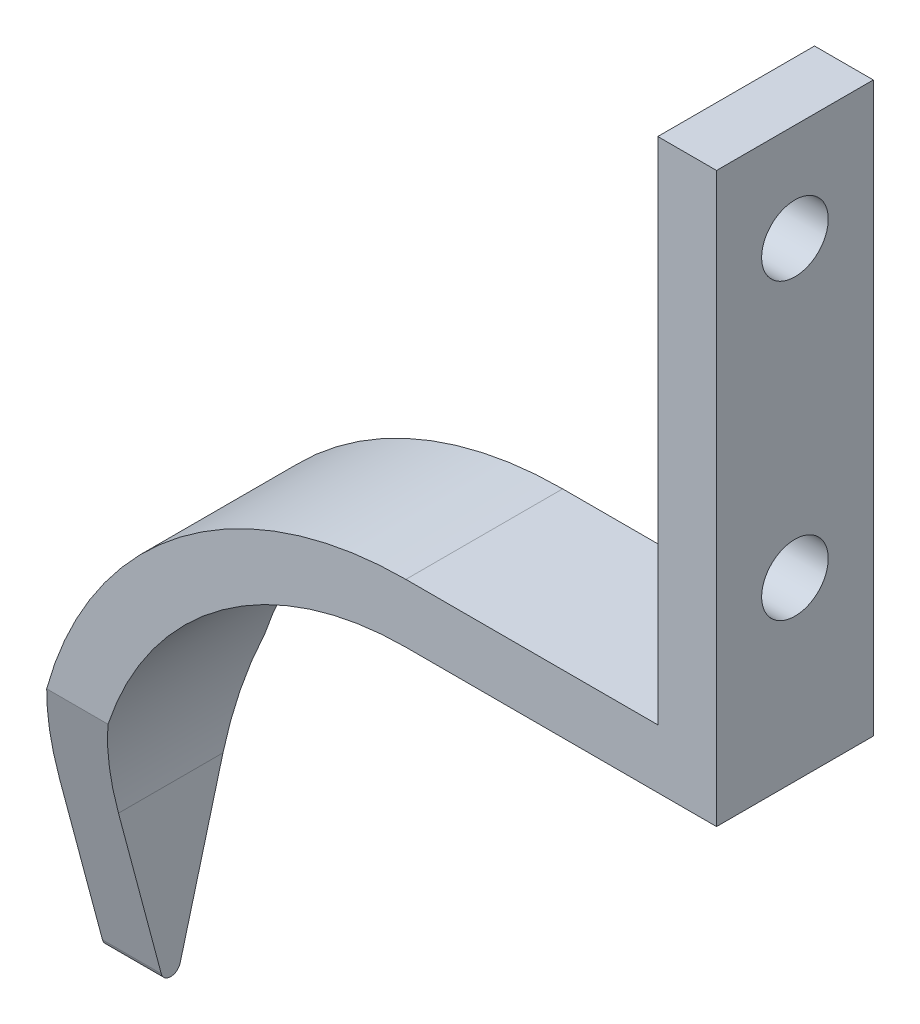
SolidWorks part; units mm, degrees
ref_plane "Front" through (0, 0, 0) normal (0, 0, 1) x (1, 0, 0)
ref_plane "Top" through (0, 0, 0) normal (0, 1, 0) x (1, 0, 0)
ref_plane "Right" through (0, 0, 0) normal (1, 0, 0) x (0, 0, -1)
ref_plane "Plane1" through (0, 0, 0) normal (0, 0, -1) x (-1, 0, 0)
sketch "Sketch1" plane through (0, 0, 0) normal (0, 0, -1) x (-1, 0, 0)
  line L1 (24.145, 100) -> (24.145, 27.967) construction
  line L2 (24.145, 100) -> (24.145, 71)
  line L3 (24.145, 71) -> (40, 71)
  line L7 (27.145, 68) -> (40, 68) construction
  line L8 (-17.145, 68) -> (17.145, 68) construction
  line L9 (-40, 68) -> (-27.145, 68) construction
  line L11 (53, 36.8203) -> (53, -69.4315) construction
  line L12 (40, 74) -> (27.145, 74)
  line L13 (27.145, 74) -> (27.145, 100)
  line L14 (27.145, 100) -> (24.145, 100)
  line L15 (56, 55) -> (56, 45)
  line L16 (56, 45) -> (59, 45)
  line L17 (59, 45) -> (59, 55)
  arc A1 (53, 55) -> (40, 68) centre (40, 55) ccw construction
  arc A2 (56, 55) -> (40, 71) centre (40, 55) ccw
  arc A3 (59, 55) -> (40, 74) centre (40, 55) ccw
  point P10 (32.0725, 71)
  dimension "D1" = 3
  dimension "D4" = 3
  dimension "D5" = 10
  dimension "D2" = 3
  dimension "D3" = 3
extrude "Boss-Extrude1" add sketch "Sketch1" along normal mid plane 8 contours L17 A3 L12 L13 L14 L2 L3 A2 L15 L16
sketch "Sketch2" plane through (-59, 0, 0) normal (-1, 0, 0) x (0, 0, 1)
  line L0 (4, 55) -> (4, 74) construction
  line L1 (-4, 74) -> (-4, 55) construction
  line L2 (4, 45) -> (4, 55) construction
  line L3 (-4, 45) -> (4, 45) construction
  line L4 (-4, 45) -> (-4, 55) construction
  line L5 (4, 55) -> (4, 74)
  line L6 (-4, 74) -> (-4, 55)
  line L7 (4, 45) -> (4, 55)
  line L8 (-4, 45) -> (4, 45)
  line L9 (-4, 45) -> (-4, 55)
  line L10 (0, 45) -> (-4, 60)
  line L11 (-4, 60) -> (4, 60)
  line L12 (4, 60) -> (0, 45)
  line M6 (4, 45) -> (4, 55)
  line M7 (4, 55) -> (-4, 55)
  line M8 (-4, 55) -> (-4, 45)
  line M9 (-4, 45) -> (4, 45)
  dimension "D1" = 15
extrude "Cut-Extrude1" cut sketch "Sketch2" against normal through all contours L10 M9 M7 M8 | L10 L6 M7 | L12 L8 M7 M6 | L5 L12 M7
fillet "Fillet1" radius 0.5 1 edges at (-57.5, 45, 0)
sketch "Sketch3" plane through (-27.145, 0, 0) normal (-1, 0, 0) x (0, 0, 1)
  line L4 (4, 74) -> (4, 100)
  line L5 (4, 100) -> (-4, 100)
  line L6 (-4, 100) -> (-4, 74)
  line L7 (-4, 74) -> (4, 74)
  line L8 (4, 74) -> (4, 100)
  line L9 (4, 100) -> (-4, 100)
  line L10 (-4, 100) -> (-4, 74)
  line L11 (-4, 74) -> (4, 74)
  circle A0 centre (0, 80) radius 1.7 construction
  circle A1 centre (0, 80) radius 1.7
  circle A2 centre (0, 95) radius 1.7 construction
  circle A3 centre (0, 95) radius 1.7
  dimension "D1" = 0
extrude "Cut-Extrude2" cut sketch "Sketch3" against normal through all contours A1 | A3
